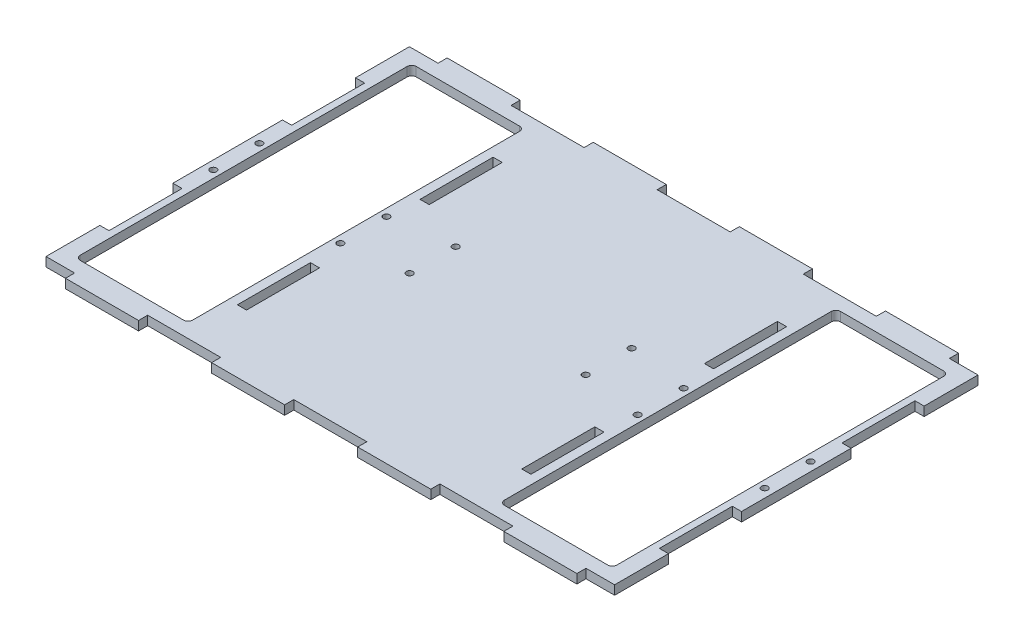
SolidWorks part; units mm, degrees
material "Acrylic (Medium-high impact)"
ref_plane "Front Plane" through (0, 0, 0) normal (0, 0, 1) x (1, 0, 0)
ref_plane "Top Plane" through (0, 0, 0) normal (0, 1, 0) x (1, 0, 0)
ref_plane "Right Plane" through (0, 0, 0) normal (1, 0, 0) x (0, 0, -1)
sketch "Sketch2" plane through (0, 0, 0) normal (0, 1, 0) x (1, 0, 0)
  line L0 (-147.5, 0) -> (147.5, 0) construction
  line L5 (-185, 195.2) -> (185, 195.2) construction
  line L6 (-197.7, -132.7) -> (197.7, -132.7)
  line L13 (110, 120) -> (185, 120)
  line L14 (110, 120) -> (110, -120)
  line L15 (110, -120) -> (185, -120)
  line L16 (185, 120) -> (185, -120)
  line L17 (110, 120) -> (185, -120) construction
  line L18 (110, -120) -> (185, 120) construction
  line L19 (-185, 120) -> (-110, 120)
  line L20 (-185, 120) -> (-185, -120)
  line L21 (-185, -120) -> (-110, -120)
  line L22 (-110, 120) -> (-110, -120)
  line L23 (-185, 120) -> (-110, -120) construction
  line L24 (-185, -120) -> (-110, 120) construction
  line L26 (-110, -37.5) -> (110, -37.5)
  line L27 (-110, -37.5) -> (-110, 37.5)
  line L28 (-110, 37.5) -> (110, 37.5)
  line L29 (110, -37.5) -> (110, 37.5)
  line L30 (-110, -37.5) -> (110, 37.5) construction
  line L31 (-110, 37.5) -> (110, -37.5) construction
  line L41 (-197.7, -132.7) -> (-197.7, 132.7)
  line L42 (-185, 132.7) -> (185, 132.7) construction
  line L43 (197.7, -132.7) -> (197.7, 132.7)
  line L44 (-197.7, -132.7) -> (197.7, 132.7) construction
  line L45 (-197.7, 132.7) -> (197.7, -132.7) construction
  line L47 (-197.7, 132.7) -> (-197.7, 257.7)
  line L48 (-197.7, 257.7) -> (-185, 257.7)
  line L49 (-185, 132.7) -> (-185, 257.7)
  line L51 (185, 132.7) -> (185, 257.7)
  line L52 (185, 257.7) -> (197.7, 257.7)
  line L53 (197.7, 132.7) -> (197.7, 257.7)
  line L54 (-185, 132.7) -> (185, 132.7)
  line L55 (223.1, 132.7) -> (223.1, 283.1)
  line L56 (159.6, 283.1) -> (223.1, 283.1)
  line L57 (159.6, 158.1) -> (159.6, 283.1)
  line L58 (-159.6, 158.1) -> (159.6, 158.1)
  line L59 (-159.6, 158.1) -> (-159.6, 283.1)
  line L60 (-223.1, 283.1) -> (-159.6, 283.1)
  line L61 (-223.1, 132.7) -> (-223.1, 283.1)
  line L62 (-223.1, -158.1) -> (-223.1, 132.7)
  line L63 (-223.1, -158.1) -> (223.1, -158.1)
  line L64 (223.1, -158.1) -> (223.1, 132.7)
  circle A0 centre (0, 308.1) radius 150
  point P2 (0, 0)
  point P13 (147.5, 0)
  point P18 (-147.5, 0)
  point P23 (0, 0)
  point P24 (0, 0)
  point P35 (0, 195.2)
  dimension "D1" = 300
  dimension "D2" = 75
  dimension "D3" = 240
  dimension "D4" = 75
  dimension "D5" = 220
  dimension "D6" = 12.7
  dimension "D7" = 12.7
  dimension "D8" = 12.7
  dimension "D9" = 125
  dimension "D10" = 25.4
sketch "Sketch5" plane through (0, 0, 0) normal (0, 1, 0) x (1, 0, 0)
  line L1 (197.7, -132.7) -> (-197.7, -132.7)
  line L2 (197.7, -132.7) -> (197.7, 132.7)
  line L3 (197.7, 132.7) -> (-197.7, 132.7)
  line L4 (-197.7, -132.7) -> (-197.7, 132.7)
extrude "Boss-Extrude3" add sketch "Sketch5" along normal blind 6.35
sketch "Sketch6" plane through (0, 6.35, 0) normal (0, 1, 0) x (1, 0, 0)
  line L0 (-185, 120) -> (-110, 120) construction
  line L1 (-185, 120) -> (-185, -120) construction
  line L2 (-185, -120) -> (-110, -120) construction
  line L3 (-110, 120) -> (-110, -120) construction
  line L4 (110, 120) -> (110, -120) construction
  line L5 (110, 120) -> (185, 120) construction
  line L6 (185, 120) -> (185, -120) construction
  line L7 (110, -120) -> (185, -120) construction
  line L8 (-185, 120) -> (-110, 120)
  line L9 (-185, 120) -> (-185, -120)
  line L10 (-185, -120) -> (-110, -120)
  line L11 (-110, 120) -> (-110, -120)
  line L12 (110, 120) -> (110, -120)
  line L13 (110, 120) -> (185, 120)
  line L14 (185, 120) -> (185, -120)
  line L15 (110, -120) -> (185, -120)
  line L16 (108.4125, 121.5875) -> (108.4125, -121.5875)
  line L17 (108.4125, -121.5875) -> (186.5875, -121.5875)
  line L18 (186.5875, 121.5875) -> (186.5875, -121.5875)
  line L19 (108.4125, 121.5875) -> (186.5875, 121.5875)
  line L20 (-108.4125, 121.5875) -> (-108.4125, -121.5875)
  line L21 (-186.5875, -121.5875) -> (-108.4125, -121.5875)
  line L22 (-186.5875, 121.5875) -> (-186.5875, -121.5875)
  line L23 (-186.5875, 121.5875) -> (-108.4125, 121.5875)
  dimension "D1" = 1.5875
extrude "Cut-Extrude1" cut sketch "Sketch6" against normal blind 6.35 contours L12 L15 L14 L13 | L19 L16 L17 L18 L15 L12 L13 L14 | L11 L8 L9 L10 | L23 L22 L21 L20 L8 L11 L10 L9
sketch "Sketch7" plane through (0, 6.35, 0) normal (0, 1, 0) x (1, 0, 0)
  arc A0 (191.675, -14.35) -> (191.043, -17.5242) centre (191.675, -16) ccw construction
  arc A1 (192.307, -14.4758) -> (191.675, -14.35) centre (191.675, -16) ccw construction
  arc A2 (191.675, -17.65) -> (192.307, -14.4758) centre (191.675, -16) ccw construction
  arc A3 (191.043, -17.5242) -> (191.675, -17.65) centre (191.675, -16) ccw construction
  arc A4 (191.675, 17.65) -> (191.043, 14.4758) centre (191.675, 16) ccw construction
  arc A5 (192.307, 17.5242) -> (191.675, 17.65) centre (191.675, 16) ccw construction
  arc A6 (191.675, 14.35) -> (192.307, 17.5242) centre (191.675, 16) ccw construction
  arc A7 (191.043, 14.4758) -> (191.675, 14.35) centre (191.675, 16) ccw construction
  arc A8 (103.325, -14.35) -> (102.693, -17.5242) centre (103.325, -16) ccw construction
  arc A9 (103.957, -14.4758) -> (103.325, -14.35) centre (103.325, -16) ccw construction
  arc A10 (103.325, -17.65) -> (103.957, -14.4758) centre (103.325, -16) ccw construction
  arc A11 (102.693, -17.5242) -> (103.325, -17.65) centre (103.325, -16) ccw construction
  arc A12 (103.325, 17.65) -> (102.693, 14.4758) centre (103.325, 16) ccw construction
  arc A13 (103.957, 17.5242) -> (103.325, 17.65) centre (103.325, 16) ccw construction
  arc A14 (103.325, 14.35) -> (103.957, 17.5242) centre (103.325, 16) ccw construction
  arc A15 (102.693, 14.4758) -> (103.325, 14.35) centre (103.325, 16) ccw construction
  arc A16 (-103.325, 17.65) -> (-103.957, 14.4758) centre (-103.325, 16) ccw construction
  arc A17 (-102.693, 17.5242) -> (-103.325, 17.65) centre (-103.325, 16) ccw construction
  arc A18 (-103.325, 14.35) -> (-102.693, 17.5242) centre (-103.325, 16) ccw construction
  arc A19 (-103.957, 14.4758) -> (-103.325, 14.35) centre (-103.325, 16) ccw construction
  arc A20 (-103.325, -14.35) -> (-103.957, -17.5242) centre (-103.325, -16) ccw construction
  arc A21 (-102.693, -14.4758) -> (-103.325, -14.35) centre (-103.325, -16) ccw construction
  arc A22 (-103.325, -17.65) -> (-102.693, -14.4758) centre (-103.325, -16) ccw construction
  arc A23 (-103.957, -17.5242) -> (-103.325, -17.65) centre (-103.325, -16) ccw construction
  arc A24 (-191.675, -14.35) -> (-192.307, -17.5242) centre (-191.675, -16) ccw construction
  arc A25 (-191.043, -14.4758) -> (-191.675, -14.35) centre (-191.675, -16) ccw construction
  arc A26 (-191.675, -17.65) -> (-191.043, -14.4758) centre (-191.675, -16) ccw construction
  arc A27 (-192.307, -17.5242) -> (-191.675, -17.65) centre (-191.675, -16) ccw construction
  arc A28 (-191.675, 14.35) -> (-191.043, 17.5242) centre (-191.675, 16) ccw construction
  arc A29 (-192.307, 14.4758) -> (-191.675, 14.35) centre (-191.675, 16) ccw construction
  arc A30 (-191.675, 17.65) -> (-192.307, 14.4758) centre (-191.675, 16) ccw construction
  arc A31 (-191.043, 17.5242) -> (-191.675, 17.65) centre (-191.675, 16) ccw construction
  circle A32 centre (-61.175, -10) radius 2.25 construction
  circle A33 centre (-61.175, 22) radius 2.25 construction
  circle A34 centre (61.175, 22) radius 2.25 construction
  circle A35 centre (61.175, -10) radius 2.25 construction
  arc A36 (191.675, -14.35) -> (191.043, -17.5242) centre (191.675, -16) ccw construction
  arc A37 (192.307, -14.4758) -> (191.675, -14.35) centre (191.675, -16) ccw construction
  arc A38 (191.675, -17.65) -> (192.307, -14.4758) centre (191.675, -16) ccw construction
  arc A39 (191.043, -17.5242) -> (191.675, -17.65) centre (191.675, -16) ccw construction
  arc A40 (191.675, 17.65) -> (191.043, 14.4758) centre (191.675, 16) ccw construction
  arc A41 (192.307, 17.5242) -> (191.675, 17.65) centre (191.675, 16) ccw construction
  arc A42 (191.675, 14.35) -> (192.307, 17.5242) centre (191.675, 16) ccw construction
  arc A43 (191.043, 14.4758) -> (191.675, 14.35) centre (191.675, 16) ccw construction
  arc A44 (103.325, -14.35) -> (102.693, -17.5242) centre (103.325, -16) ccw construction
  arc A45 (103.957, -14.4758) -> (103.325, -14.35) centre (103.325, -16) ccw construction
  arc A46 (103.325, -17.65) -> (103.957, -14.4758) centre (103.325, -16) ccw construction
  arc A47 (102.693, -17.5242) -> (103.325, -17.65) centre (103.325, -16) ccw construction
  arc A48 (103.325, 17.65) -> (102.693, 14.4758) centre (103.325, 16) ccw construction
  arc A49 (103.957, 17.5242) -> (103.325, 17.65) centre (103.325, 16) ccw construction
  arc A50 (103.325, 14.35) -> (103.957, 17.5242) centre (103.325, 16) ccw construction
  arc A51 (102.693, 14.4758) -> (103.325, 14.35) centre (103.325, 16) ccw construction
  arc A52 (-103.325, 17.65) -> (-103.957, 14.4758) centre (-103.325, 16) ccw construction
  arc A53 (-102.693, 17.5242) -> (-103.325, 17.65) centre (-103.325, 16) ccw construction
  arc A54 (-103.325, 14.35) -> (-102.693, 17.5242) centre (-103.325, 16) ccw construction
  arc A55 (-103.957, 14.4758) -> (-103.325, 14.35) centre (-103.325, 16) ccw construction
  arc A56 (-103.325, -14.35) -> (-103.957, -17.5242) centre (-103.325, -16) ccw construction
  arc A57 (-102.693, -14.4758) -> (-103.325, -14.35) centre (-103.325, -16) ccw construction
  arc A58 (-103.325, -17.65) -> (-102.693, -14.4758) centre (-103.325, -16) ccw construction
  arc A59 (-103.957, -17.5242) -> (-103.325, -17.65) centre (-103.325, -16) ccw construction
  arc A60 (-191.675, -14.35) -> (-192.307, -17.5242) centre (-191.675, -16) ccw construction
  arc A61 (-191.043, -14.4758) -> (-191.675, -14.35) centre (-191.675, -16) ccw construction
  arc A62 (-191.675, -17.65) -> (-191.043, -14.4758) centre (-191.675, -16) ccw construction
  arc A63 (-192.307, -17.5242) -> (-191.675, -17.65) centre (-191.675, -16) ccw construction
  arc A64 (-191.675, 14.35) -> (-191.043, 17.5242) centre (-191.675, 16) ccw construction
  arc A65 (-192.307, 14.4758) -> (-191.675, 14.35) centre (-191.675, 16) ccw construction
  arc A66 (-191.675, 17.65) -> (-192.307, 14.4758) centre (-191.675, 16) ccw construction
  arc A67 (-191.043, 17.5242) -> (-191.675, 17.65) centre (-191.675, 16) ccw construction
  circle A68 centre (-61.175, -10) radius 2.25 construction
  circle A69 centre (-61.175, 22) radius 2.25 construction
  circle A70 centre (61.175, 22) radius 2.25 construction
  circle A71 centre (61.175, -10) radius 2.25 construction
hole_wizard "Ø4.0mm Dowel Hole1" positions "Sketch8" profile "Sketch9" hole size "Ø4.0" standard "ANSI Metric" end condition through all
sketch "Sketch8" plane through (0, 6.35, 0) normal (0, 1, 0) x (1, 0, 0)
  point P0 (191.675, -16)
  point P3 (191.675, 16)
  point P6 (103.325, -16)
  point P9 (103.325, 16)
  point P12 (-191.675, -16)
  point P15 (-191.675, 16)
  point P18 (-103.325, -16)
  point P21 (-103.325, 16)
  point P24 (-61.175, -10)
  point P27 (-61.175, 22)
  point P30 (61.175, 22)
  point P33 (61.175, -10)
sketch "Sketch9" plane through (191.675, 6.35, 16) normal (1, 0, 0) x (0, 0, 1)
  line L0 (0, 0) -> (0, 6.35)
  line L1 (0, 6.35) -> (2.25, 6.35)
  line L2 (2.25, 6.35) -> (2.25, 0)
  line L5 (2.25, 0) -> (0, 0)
  line L11 (0, -6.35) -> (0, 107.95) construction
  dimension "Thru Hole Dia." = 4.5
  dimension "Thru Hole Depth" = 6.35
sketch "Sketch10" plane through (0, 0, 0) normal (0, -1, 0) x (1, 0, 0)
  line L0 (-191.35, -126.35) -> (191.35, -126.35)
  line L1 (191.35, -126.35) -> (191.35, 126.35)
  line L2 (191.35, 126.35) -> (-191.35, 126.35)
  line L3 (-191.35, 126.35) -> (-191.35, -126.35)
  line L4 (197.7, -132.7) -> (197.7, 132.7)
  line L5 (197.7, 132.7) -> (-197.7, 132.7)
  line L6 (-197.7, 132.7) -> (-197.7, -132.7)
  line L7 (-197.7, -132.7) -> (197.7, -132.7)
  line L8 (197.7, -132.7) -> (197.7, 132.7)
  line L9 (197.7, 132.7) -> (-197.7, 132.7)
  line L10 (-197.7, 132.7) -> (-197.7, -132.7)
  line L11 (-197.7, -132.7) -> (197.7, -132.7)
  line L12 (102.0625, -126.35) -> (102.0625, 126.35)
  line L13 (-102.0625, -126.35) -> (-102.0625, 126.35)
  line L14 (108.4125, -126.35) -> (108.4125, 126.35)
  line L15 (-108.4125, -126.35) -> (-108.4125, 126.35)
  line L16 (108.4125, -121.5875) -> (108.4125, 121.5875) construction
  line L17 (-108.4125, -121.5875) -> (-108.4125, 121.5875) construction
  line L18 (95.7125, -126.35) -> (95.7125, 126.35)
  line L19 (-95.7125, -126.35) -> (-95.7125, 126.35)
  line L20 (197.7, 0) -> (-197.7, 0) construction
  line L21 (102.0625, -88.9) -> (95.7125, -88.9)
  line L22 (102.0625, -88.9) -> (102.0625, -38.1)
  line L23 (102.0625, -38.1) -> (95.7125, -38.1)
  line L24 (95.7125, -88.9) -> (95.7125, -38.1)
  line L25 (102.0625, 38.1) -> (95.7125, 38.1)
  line L26 (102.0625, 38.1) -> (102.0625, 88.9)
  line L27 (102.0625, 88.9) -> (95.7125, 88.9)
  line L28 (95.7125, 38.1) -> (95.7125, 88.9)
  line L29 (-102.0625, -88.9) -> (-95.7125, -88.9)
  line L30 (-102.0625, -88.9) -> (-102.0625, -38.1)
  line L31 (-102.0625, -38.1) -> (-95.7125, -38.1)
  line L32 (-95.7125, -88.9) -> (-95.7125, -38.1)
  line L33 (-95.7125, 88.9) -> (-102.0625, 88.9)
  line L34 (-95.7125, 88.9) -> (-95.7125, 38.1)
  line L35 (-95.7125, 38.1) -> (-102.0625, 38.1)
  line L36 (-102.0625, 88.9) -> (-102.0625, 38.1)
  line L37 (76.2, 126.35) -> (25.4, 126.35)
  line L38 (76.2, 126.35) -> (76.2, 132.7)
  line L39 (76.2, 132.7) -> (25.4, 132.7)
  line L40 (25.4, 126.35) -> (25.4, 132.7)
  line L41 (-25.4, 126.35) -> (-76.2, 126.35)
  line L42 (-25.4, 126.35) -> (-25.4, 132.7)
  line L43 (-25.4, 132.7) -> (-76.2, 132.7)
  line L44 (-76.2, 126.35) -> (-76.2, 132.7)
  line L45 (177.8, 126.35) -> (127, 126.35)
  line L46 (177.8, 126.35) -> (177.8, 132.7)
  line L47 (177.8, 132.7) -> (127, 132.7)
  line L48 (127, 126.35) -> (127, 132.7)
  line L49 (-127, 126.35) -> (-177.8, 126.35)
  line L50 (-127, 126.35) -> (-127, 132.7)
  line L51 (-127, 132.7) -> (-177.8, 132.7)
  line L52 (-177.8, 126.35) -> (-177.8, 132.7)
  line L53 (-127, -132.7) -> (-177.8, -132.7)
  line L54 (-177.8, -126.35) -> (-177.8, -132.7)
  line L55 (-127, -126.35) -> (-177.8, -126.35)
  line L56 (-127, -126.35) -> (-127, -132.7)
  line L57 (-25.4, -132.7) -> (-76.2, -132.7)
  line L58 (-76.2, -126.35) -> (-76.2, -132.7)
  line L59 (-25.4, -126.35) -> (-76.2, -126.35)
  line L60 (-25.4, -126.35) -> (-25.4, -132.7)
  line L61 (76.2, -132.7) -> (25.4, -132.7)
  line L62 (25.4, -126.35) -> (25.4, -132.7)
  line L63 (76.2, -126.35) -> (25.4, -126.35)
  line L64 (76.2, -126.35) -> (76.2, -132.7)
  line L65 (177.8, -132.7) -> (127, -132.7)
  line L66 (127, -126.35) -> (127, -132.7)
  line L67 (177.8, -126.35) -> (127, -126.35)
  line L68 (177.8, -126.35) -> (177.8, -132.7)
  line L69 (191.35, 126.35) -> (197.7, 126.35)
  line L70 (-191.35, 126.35) -> (-197.7, 126.35)
  line L71 (-191.35, -126.35) -> (-197.7, -126.35)
  line L72 (191.35, -126.35) -> (197.7, -126.35)
  line M31 (197.7, -132.7) -> (197.7, 132.7)
  line M32 (197.7, 132.7) -> (-197.7, 132.7)
  line M33 (-197.7, 132.7) -> (-197.7, -132.7)
  line M34 (-197.7, -132.7) -> (197.7, -132.7)
  dimension "D3" = 6.35
  dimension "D4" = 6.35
  dimension "D5" = 6.35
  dimension "D6" = 6.35
  dimension "D7" = 50.8
  dimension "D8" = 50.8
  dimension "D9" = 76.2
  dimension "D10" = 38.1
  dimension "D11" = 50.8
  dimension "D12" = 50.8
  dimension "D13" = 50.8
  dimension "D14" = 25.4
  dimension "D15" = 50.8
  dimension "D16" = 50.8
  dimension "D17" = 50.8
  dimension "D18" = 50.8
  dimension "D1" = 0
  dimension "D2" = 6.35
extrude "Cut-Extrude2" cut sketch "Sketch10" against normal blind 6.35 contours L12 L23 L18 L21 | L12 L27 L18 L25 | L35 L19 L33 L13 | L31 L13 L29 L19 | L2 L69 L8 L46 M32 | L2 L48 L38 M32 | L42 L2 L40 M32 | L50 L2 L44 M32 | L70 L2 L52 M32 M33 | L0 L71 L54 M33 M34 | L58 L0 L56 M34 | L62 L0 L60 M34 | L66 L0 L64 M34 | L72 L0 L68 M34 M31
sketch "Sketch11" plane through (197.7, 0, 0) normal (1, 0, 0) x (0, 0, -1)
  line L0 (-88.9, 0) -> (-38.1, 0) construction
  line L1 (-38.1, 0) -> (-38.1, 6.35) construction
  line L2 (-38.1, 6.35) -> (-88.9, 6.35) construction
  line L3 (-88.9, 6.35) -> (-88.9, 0) construction
  line L4 (38.1, 0) -> (88.9, 0) construction
  line L5 (88.9, 0) -> (88.9, 6.35) construction
  line L6 (88.9, 6.35) -> (38.1, 6.35) construction
  line L7 (38.1, 6.35) -> (38.1, 0) construction
  line L8 (-88.9, 0) -> (-38.1, 0)
  line L9 (-38.1, 0) -> (-38.1, 6.35)
  line L10 (-38.1, 6.35) -> (-88.9, 6.35)
  line L11 (-88.9, 6.35) -> (-88.9, 0)
  line L12 (38.1, 0) -> (88.9, 0)
  line L13 (88.9, 0) -> (88.9, 6.35)
  line L14 (88.9, 6.35) -> (38.1, 6.35)
  line L15 (38.1, 6.35) -> (38.1, 0)
extrude "Cut-Extrude3" cut sketch "Sketch11" against normal blind 6.35
mirror "Mirror1" about plane through (0, 0, 0) normal (1, 0, 0) of "Cut-Extrude3"
sketch "Sketch12" plane through (0, 0, 0) normal (0, -1, 0) x (1, 0, 0)
  line L0 (108.4125, -121.5875) -> (108.4125, 121.5875) construction
  line L1 (186.5875, -121.5875) -> (108.4125, -121.5875)
  line L2 (186.5875, -121.5875) -> (186.5875, -116.825)
  line L3 (186.5875, -116.825) -> (108.4125, -116.825)
  line L4 (108.4125, -121.5875) -> (108.4125, -116.825)
  line L5 (186.5875, -121.5875) -> (186.5875, 121.5875) construction
  line L6 (108.4125, 121.5875) -> (186.5875, 121.5875)
  line L7 (108.4125, 121.5875) -> (108.4125, 116.825)
  line L8 (108.4125, 116.825) -> (186.5875, 116.825)
  line L9 (186.5875, 121.5875) -> (186.5875, 116.825)
  line L10 (-186.5875, -121.5875) -> (-186.5875, 121.5875) construction
  line L11 (-108.4125, 121.5875) -> (-186.5875, 121.5875)
  line L12 (-108.4125, 121.5875) -> (-108.4125, 116.825)
  line L13 (-108.4125, 116.825) -> (-186.5875, 116.825)
  line L14 (-186.5875, 121.5875) -> (-186.5875, 116.825)
  line L15 (-108.4125, -121.5875) -> (-108.4125, 121.5875) construction
  line L16 (-186.5875, -121.5875) -> (-108.4125, -121.5875)
  line L17 (-186.5875, -121.5875) -> (-186.5875, -116.825)
  line L18 (-186.5875, -116.825) -> (-108.4125, -116.825)
  line L19 (-108.4125, -121.5875) -> (-108.4125, -116.825)
  dimension "D1" = 4.7625
extrude "Boss-Extrude4" add sketch "Sketch12" against normal up to surface (6.35 mm away) up to face at (98.8875, 6.35, 63.5)
fillet "Fillet1" radius 3.175 8 edges at (-186.5875, 3.175, 116.825) (-108.4125, 3.175, 116.825) (-186.5875, 3.175, -116.825) (-108.4125, 3.175, -116.825) (108.4125, 3.175, 116.825) (186.5875, 3.175, 116.825) (108.4125, 3.175, -116.825) (186.5875, 3.175, -116.825)
